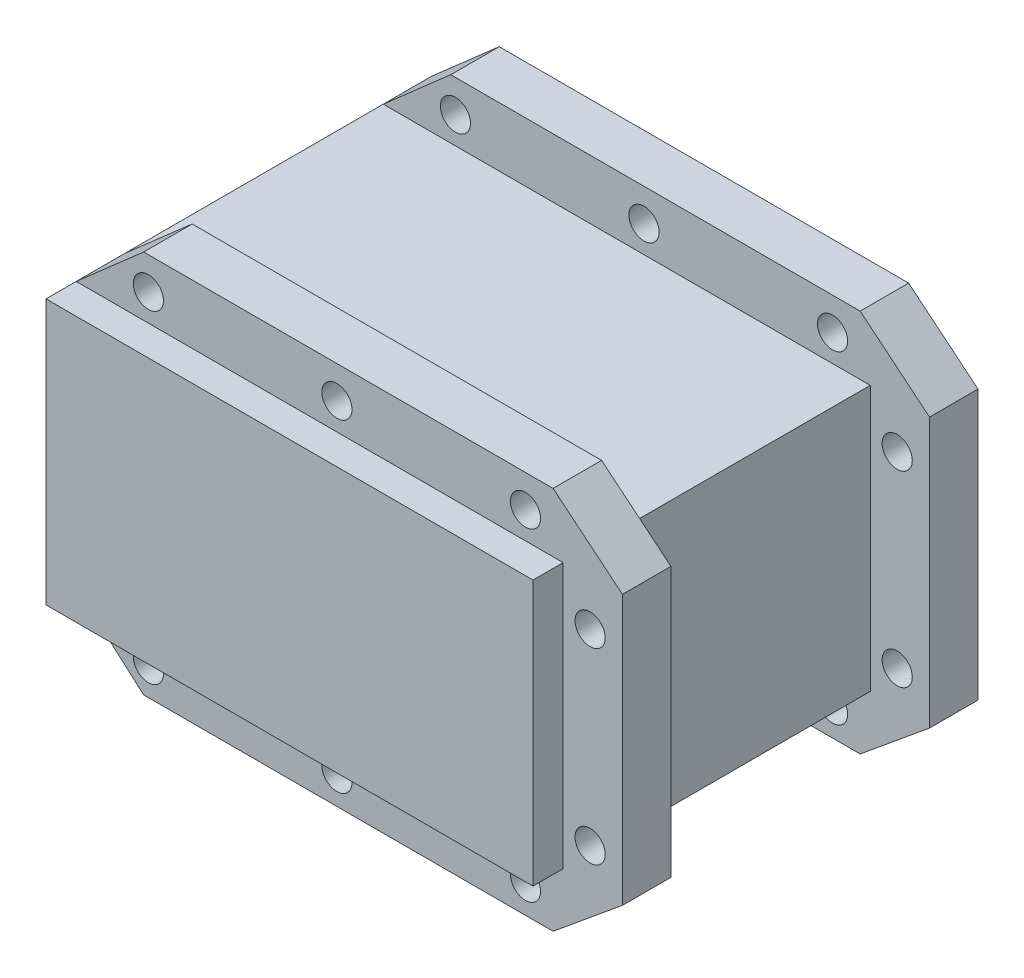
SolidWorks part; units mm, degrees
ref_plane "Front Plane" through (0, 0, 0) normal (0, 0, 1) x (1, 0, 0)
ref_plane "Top Plane" through (0, 0, 0) normal (0, 1, 0) x (1, 0, 0)
ref_plane "Right Plane" through (0, 0, 0) normal (1, 0, 0) x (0, 0, -1)
sketch "Sketch1" plane through (0, 0, 0) normal (0, 0, 1) x (1, 0, 0)
  line L1 (0, 0) -> (45.2, 0)
  line L2 (0, 0) -> (0, 24.6)
  line L3 (0, 24.6) -> (45.2, 24.6)
  line L4 (45.2, 0) -> (45.2, 24.6)
  dimension "D1" = 45.2
  dimension "D2" = 24.6
extrude "Boss-Extrude1" add sketch "Sketch1" along normal blind 35.8
ref_plane "Plane4" through (0, 0, 33) normal (0, 0, 1) x (1, 0, 0)
sketch "Sketch3" plane through (0, 0, 33) normal (0, 0, 1) x (1, 0, 0)
  line L0 (0, 24.6) -> (6.265, 30.1)
  line L1 (6.265, 30.1) -> (44.265, 30.1)
  line L2 (44.265, 30.1) -> (50.7, 24.8)
  line L3 (50.7, 24.8) -> (50.7, -0.2)
  line L4 (50.7, -0.2) -> (44.265, -5.5)
  line L5 (44.265, -5.5) -> (6.265, -5.5)
  line L7 (0, 0) -> (45.2, 0)
  line L8 (45.2, 0) -> (45.2, 24.6)
  line L9 (45.2, 24.6) -> (0, 24.6)
  line L10 (0, 0) -> (6.265, -5.5)
  dimension "D1" = 5.5
  dimension "D2" = 5.5
  dimension "D3" = 5.5
  dimension "D4" = 38
  dimension "D5" = 38
  dimension "D6" = 25
extrude "Boss-Extrude2" add sketch "Sketch3" against normal blind 4.5
sketch "Sketch4" plane through (0, 0, 33) normal (0, 0, 1) x (1, 0, 0)
  line L0 (44.265, 30.1) -> (6.265, 30.1) construction
  line L1 (0, 24.6) -> (0, 0) construction
  circle A0 centre (6.7, 27.1) radius 1.4
  point P2 (6.7, 28.5)
  point P5 (5.3, 27.1)
  dimension "D1" = 2.8
  dimension "D2" = 1.6
  dimension "D3" = 5.3
extrude "Cut-Extrude1" cut sketch "Sketch4" against normal through all
pattern_linear "LPattern1" count 3 spacing 17.5 along (1, 0, 0) count 2 spacing 30 along (0, -1, 0) of "Cut-Extrude1"
sketch "Sketch6" plane through (0, 0, 33) normal (0, 0, 1) x (1, 0, 0)
  line L0 (50.7, -0.2) -> (50.7, 24.8) construction
  line L1 (47.7, 20.5) -> (47.7, 9.4008) construction
  line L2 (47.7, 9.4008) -> (47.7, 3.1) construction
  line L3 (0, 24.6) -> (45.2, 24.6) construction
  line L4 (45.2, 24.6) -> (0, 24.6) construction
  circle A0 centre (47.7, 20.5) radius 1.4
  circle A2 centre (47.7, 3.1) radius 1.4
  point P3 (47.7, 19.1)
  point P6 (46.3, 20.5)
  point P7 (46.3, 9.4008)
  point P8 (46.3, 3.1)
  point P9 (49.1, 20.5)
  point P14 (47.7, 4.5)
  point P15 (47.7, 21.9)
  dimension "D1" = 2.8
  dimension "D2" = 1.6
  dimension "D3" = 14.6
  dimension "D4" = 5.5
extrude "Cut-Extrude2" cut sketch "Sketch6" against normal through all
pattern_linear "LPattern2" count 2 spacing 28.5 along (0, 0, -1) of "Boss-Extrude2", "Cut-Extrude1", "LPattern1", "Cut-Extrude2"
